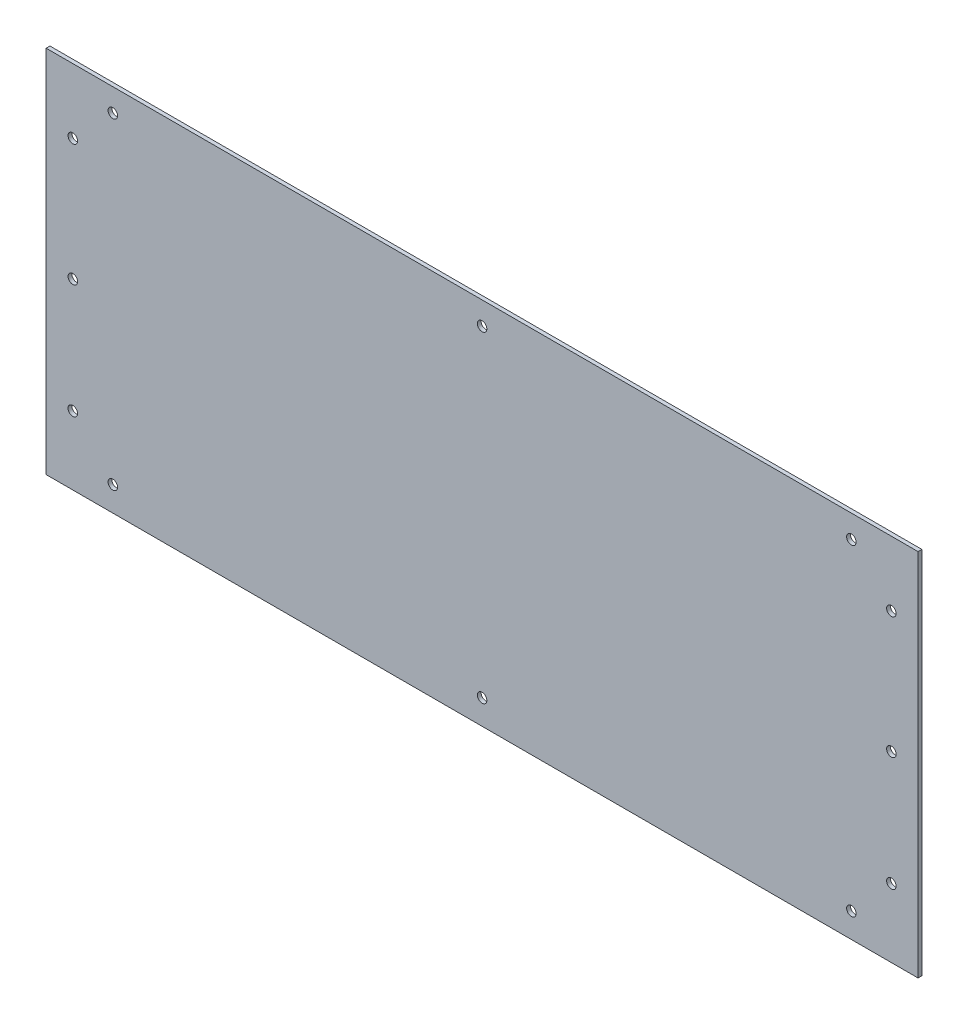
SolidWorks part; units mm, degrees
material "1345 Alloy"
ref_plane "Front Plane" through (0, 0, 0) normal (0, 0, 1) x (1, 0, 0)
ref_plane "Top Plane" through (0, 0, 0) normal (0, 1, 0) x (1, 0, 0)
ref_plane "Right Plane" through (0, 0, 0) normal (1, 0, 0) x (0, 0, -1)
sketch "Sketch1" plane through (0, 0, 0) normal (0, 0, 1) x (1, 0, 0)
  line L1 (-229, 96) -> (229, 96)
  line L2 (-229, 96) -> (-229, -96)
  line L3 (-229, -96) -> (229, -96)
  line L4 (229, 96) -> (229, -96)
  line L5 (-229, 96) -> (229, -96) construction
  line L6 (-229, -96) -> (229, 96) construction
  point P0 (0, 0)
  dimension "D1" = 458
  dimension "D2" = 192
extrude "Boss-Extrude1" add sketch "Sketch1" along normal blind 2
sketch "Sketch2" plane through (0, 0, 2) normal (0, 0, 1) x (1, 0, 0)
  line L0 (-229, 96) -> (-229, 86) construction
  line L1 (-229, 96) -> (-194, 96) construction
  line L2 (-194, 96) -> (-194, 86) construction
  line L3 (-194, 86) -> (-229, 86) construction
  line L4 (-194, -83.0046) -> (194, -83.0046) construction
  line L6 (0, -83) -> (0, -96) construction
  line L7 (194, -96.0046) -> (194, -83.0046) construction
  line L8 (194, 86) -> (194, 96) construction
  line L9 (-229, 0) -> (-215, 0) construction
  line L10 (-215, 0) -> (-215, 64) construction
  line L11 (-215, 0) -> (-215, -60) construction
  line L12 (229, 0) -> (215, 0) construction
  line L13 (0, 86) -> (-194, 86) construction
  line L14 (215, 64) -> (215, 96) construction
  line L15 (215, 0) -> (215, 64) construction
  line L16 (215, 0) -> (215, -60) construction
  line L17 (0, 86) -> (194, 86) construction
  line L18 (229, 96) -> (-229, 96) construction
  line L19 (-229, -96) -> (229, -96) construction
  line L22 (-215, 64) -> (-215, 96) construction
  circle A0 centre (-194, 86) radius 2.5
  circle A1 centre (-194, -83.0046) radius 2.5
  circle A2 centre (194, -83.0046) radius 2.5
  circle A3 centre (194, 86) radius 2.5
  circle A4 centre (-215, 0) radius 2.5
  circle A5 centre (-215, -60) radius 2.5
  circle A6 centre (-215, 64) radius 2.5
  circle A7 centre (215, 0) radius 2.5
  circle A8 centre (215, -60) radius 2.5
  circle A9 centre (215, 64) radius 2.5
  circle A10 centre (0, 86) radius 2.5
  circle A11 centre (0, -83) radius 2.5
  dimension "D3" = 5
  dimension "D6" = 5
  dimension "D7" = 5
  dimension "D8" = 5
  dimension "D13" = 5
  dimension "D14" = 5
  dimension "D15" = 5
  dimension "D19" = 5
  dimension "D20" = 5
  dimension "D1" = 10
  dimension "D2" = 35
  dimension "D4" = 13
  dimension "D5" = 12.9954
  dimension "D9" = 13
  dimension "D10" = 14
  dimension "D11" = 64
  dimension "D12" = 60
  dimension "D16" = 14
  dimension "D17" = 64
  dimension "D18" = 60
  dimension "D22" = 194
  dimension "D23" = 194
  dimension "D24" = 32
  dimension "D25" = 32
extrude "Cut-Extrude1" cut sketch "Sketch2" against normal through all
sketch "Sketch3" plane through (0, 0, 2) normal (0, 0, 1) x (1, 0, 0)
  line L1 (-229, 96) -> (229, 96)
  line L2 (-229, 96) -> (-229, 98)
  line L3 (-229, 98) -> (229, 98)
  line L4 (229, 96) -> (229, 98)
  dimension "D1" = 458
  dimension "D2" = 2
extrude "Boss-Extrude2" add sketch "Sketch3" against normal through all
